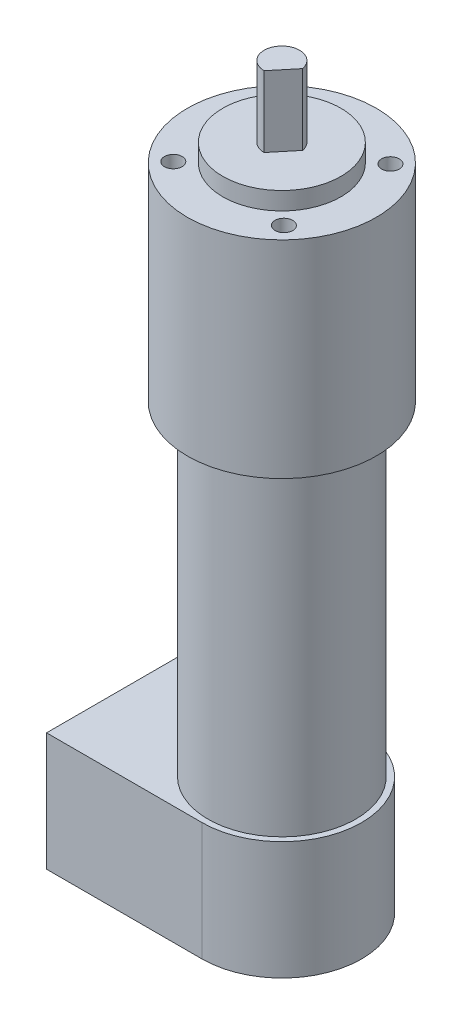
SolidWorks part; units mm, degrees
ref_plane "Plan de face" through (0, 0, 0) normal (0, 0, 1) x (1, 0, 0)
ref_plane "Plan de dessus" through (0, 0, 0) normal (0, 1, 0) x (1, 0, 0)
ref_plane "Plan de droite" through (0, 0, 0) normal (1, 0, 0) x (0, 0, -1)
sketch "Esquisse1" plane through (0, 0, 0) normal (0, 1, 0) x (1, 0, 0)
  circle A0 centre (0, 0) radius 16
  dimension "D1" = 32
extrude "Boss.-Extru.1" add sketch "Esquisse1" along normal blind 35 contours A0
sketch "Esquisse2" plane through (0, 0, 0) normal (0, -1, 0) x (1, 0, 0)
  circle A0 centre (0, 0) radius 12.5
  dimension "D1" = 25
extrude "Boss.-Extru.2" add sketch "Esquisse2" along normal blind 55
sketch "Esquisse3" plane through (0, 35, 0) normal (0, 1, 0) x (1, 0, 0)
  circle A0 centre (0, 0) radius 3
  dimension "D1" = 6
extrude "Boss.-Extru.3" add sketch "Esquisse3" along normal blind 15 contours A0
sketch "Esquisse4" plane through (0, 50, 0) normal (0, 1, 0) x (1, 0, 0)
  line L0 (2.9464, 0.5646) -> (0, -3)
  arc A0 (2.9464, 0.5646) -> (0, -3) centre (0, 0) cw
  circle A1 centre (0, 0) radius 3 construction
extrude "Enlèv. mat.-Extru.1" cut sketch "Esquisse4" against normal blind 15
sketch "Esquisse5" plane through (0, 35, 0) normal (0, 1, 0) x (1, 0, 0)
  circle A0 centre (0, 0) radius 10
  dimension "D1" = 20
extrude "Boss.-Extru.4" add sketch "Esquisse5" along normal blind 3
sketch "Esquisse6" plane through (0, 35, 0) normal (0, 1, 0) x (1, 0, 0)
  line L0 (0, 16) -> (0, -16) construction
  line L1 (16, 0) -> (-16, 0) construction
  circle A0 centre (0, 0) radius 16 construction
sketch "Esquisse8" plane through (0, 35, 0) normal (0, 1, 0) x (1, 0, 0)
  line L5 (9.3638, -9.0177) -> (-9.3638, 9.0177) construction
  line L6 (9.3638, 9.0177) -> (-9.3638, -9.0177) construction
  circle A0 centre (-9.3638, 9.0177) radius 1.5
  circle A1 centre (9.3638, 9.0177) radius 1.5
  circle A2 centre (-9.3638, -9.0177) radius 1.5
  circle A3 centre (9.3638, -9.0177) radius 1.5
  point P0 (0, 0)
  dimension "D2" = 3
  dimension "D3" = 3
  dimension "D4" = 3
  dimension "D5" = 3
  dimension "D1" = 26
extrude "Enlèv. mat.-Extru.2" cut sketch "Esquisse8" against normal blind 10
sketch "Esquisse9" plane through (0, -55, 0) normal (0, -1, 0) x (1, 0, 0)
  line L0 (0, 13.5) -> (-26.3404, 13.5)
  line L1 (-26.3404, 13.5) -> (-26.3404, -13.5)
  line L2 (-26.3404, -13.5) -> (0, -13.5)
  arc A0 (0, 13.5) -> (0, -13.5) centre (0, 0) cw
  dimension "D1" = 13.5
extrude "Boss.-Extru.5" add sketch "Esquisse9" along normal blind 20
sketch "Esquisse10" plane through (-26.3404, 0, 0) normal (-1, 0, 0) x (0, 0, 1)
  line L1 (8.4905, -56.7267) -> (-8.4905, -56.7267)
  line L2 (8.4905, -56.7267) -> (8.4905, -63.9093)
  line L3 (8.4905, -63.9093) -> (-8.4905, -63.9093)
  line L4 (-8.4905, -56.7267) -> (-8.4905, -63.9093)
  line L5 (8.4905, -56.7267) -> (-8.4905, -63.9093) construction
  line L6 (8.4905, -63.9093) -> (-8.4905, -56.7267) construction
  point P0 (0, -60.318)
extrude "Enlèv. mat.-Extru.3" cut sketch "Esquisse10" against normal blind 12
sketch "Esquisse12" plane through (-14.3404, 0, 0) normal (-1, 0, 0) x (0, 0, 1)
  line L0 (-8.4905, -56.7267) -> (-8.4905, -63.9093) construction
  line L1 (-4.4905, -58.0749) -> (-3.4905, -58.0749)
  line L2 (-4.4905, -58.0749) -> (-4.4905, -59.0749)
  line L3 (-4.4905, -59.0749) -> (-3.4905, -59.0749)
  line L4 (-3.4905, -58.0749) -> (-3.4905, -59.0749)
  line L6 (-3.4905, -58.0749) -> (-3.4905, -58.7839)
  line L9 (-2.4905, -58.0749) -> (-1.4905, -58.0749)
  line L10 (-2.4905, -58.0749) -> (-2.4905, -59.0749)
  line L11 (-2.4905, -59.0749) -> (-1.4905, -59.0749)
  line L12 (-1.4905, -58.0749) -> (-1.4905, -59.0749)
  line L13 (-0.4905, -58.0749) -> (0.5095, -58.0749)
  line L14 (-0.4905, -58.0749) -> (-0.4905, -59.0749)
  line L15 (-0.4905, -59.0749) -> (0.5095, -59.0749)
  line L16 (0.5095, -58.0749) -> (0.5095, -59.0749)
  line L22 (1.5095, -58.0749) -> (2.5095, -58.0749)
  line L23 (1.5095, -58.0749) -> (1.5095, -59.0749)
  line L24 (1.5095, -59.0749) -> (2.5095, -59.0749)
  line L25 (2.5095, -58.0749) -> (2.5095, -59.0749)
  line L26 (3.5095, -58.0749) -> (4.5095, -58.0749)
  line L27 (3.5095, -58.0749) -> (3.5095, -59.0749)
  line L28 (3.5095, -59.0749) -> (4.5095, -59.0749)
  line L29 (4.5095, -58.0749) -> (4.5095, -59.0749)
  dimension "D1" = 4
  dimension "D2" = 1
  dimension "D3" = 1
  dimension "D4" = 1
  dimension "D5" = 1
  dimension "D6" = 1
  dimension "D7" = 1
  dimension "D8" = 1
  dimension "D9" = 1
  dimension "D10" = 1
  dimension "D11" = 1
  dimension "D12" = 1
  dimension "D13" = 1
  dimension "D14" = 1
  dimension "D15" = 1
extrude "Boss.-Extru.6" add sketch "Esquisse12" along normal blind 12 contours L12 L9 L10 L11 | L4 L1 L2 L3 | L16 L13 L14 L15 | L25 L22 L23 L24 | L29 L26 L27 L28
